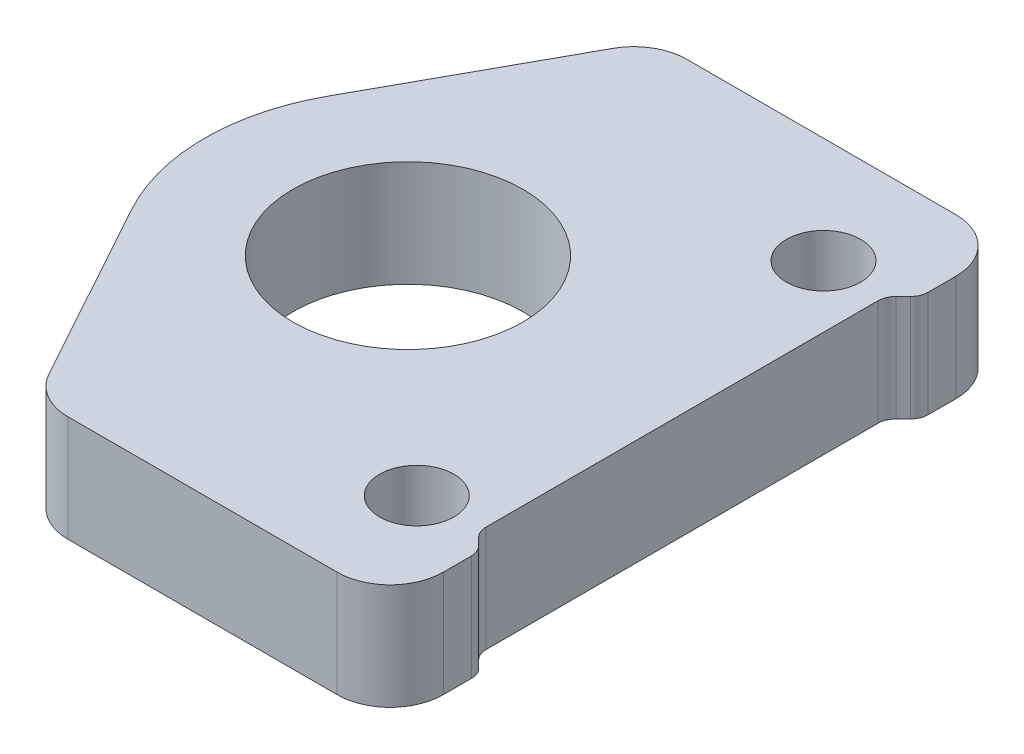
SolidWorks part; units mm, degrees
material "Thornel Mat VMA"
ref_plane "前视基准面" through (0, 0, 0) normal (0, 0, 1) x (1, 0, 0)
ref_plane "上视基准面" through (0, 0, 0) normal (0, 1, 0) x (1, 0, 0)
ref_plane "右视基准面" through (0, 0, 0) normal (1, 0, 0) x (0, 0, -1)
other "Configuration Table"
sketch "草图1" plane through (0, 0, 0) normal (0, 1, 0) x (1, 0, 0)
  line L0 (9.5, -11.5) -> (9.5, 11.5) construction
  line L2 (-14, 17.5) -> (14, 17.5)
  line L3 (-14, 17.5) -> (-14, -17.5)
  line L4 (-14, -17.5) -> (14, -17.5)
  line L5 (14, 17.5) -> (14, -17.5)
  line L6 (-14, 17.5) -> (14, -17.5) construction
  line L7 (-14, -17.5) -> (14, 17.5) construction
  circle A0 centre (9.5, 11.5) radius 2.1
  circle A1 centre (9.5, -11.5) radius 2.1
  circle A2 centre (-2.5, 0) radius 6.505
  point P4 (0, 0)
  dimension "D2" = 4.2
  dimension "D4" = 13.01
  dimension "D1" = 23
  dimension "D3" = 4.5
  dimension "D5" = 12
  dimension "D6" = 28
  dimension "D7" = 35
  dimension "D8" = 11.5
extrude "凸台-拉伸1" add sketch "草图1" along normal blind 6
sketch "草图2" plane through (0, 6, 0) normal (0, 1, 0) x (1, 0, 0)
  line L0 (9.5, 11.5) -> (9.5, -11.5) construction
  line L1 (14, 12.5) -> (13, 11.5)
  line L2 (13, 11.5) -> (18, 11.5) construction
  line L3 (13, 11.5) -> (13, -11.5) construction
  line L4 (13, -11.5) -> (18, -11.5) construction
  line L5 (18, 11.5) -> (18, -11.5) construction
  line L6 (14, -17.5) -> (14, 17.5) construction
  line L7 (13, 11.5) -> (13, -11.5)
  line L8 (13, -11.5) -> (14, -12.5)
  line L9 (14, -12.5) -> (14, 12.5)
  circle A0 centre (9.5, 11.5) radius 3.5 construction
  point P8 (13, 0)
  point P9 (9.5, 0)
  dimension "D2" = 7
  dimension "D1" = 23
  dimension "D3" = 5
  dimension "D4" = 45
  dimension "D5" = 45
extrude "切除-拉伸1" cut sketch "草图2" against normal blind 6
fillet "圆角1" radius 1 4 edges at (14, 3, 12.5) (13, 3, 11.5) (14, 3, -12.5) (13, 3, -11.5)
sketch "草图3" plane through (0, 6, 0) normal (0, 1, 0) x (1, 0, 0)
  line L0 (-14, -17.5) -> (14, -17.5) construction
  line L1 (-6, -17.5) -> (-12.5766, -5.5418)
  line L2 (-6, 17.5) -> (-12.5766, 5.5418)
  line L3 (14, 17.5) -> (-14, 17.5) construction
  line L4 (-14, 17.5) -> (-14, -17.5) construction
  line L5 (-14, -17.5) -> (14, -17.5)
  line L6 (-14, 17.5) -> (-14, -17.5)
  line L7 (14, 17.5) -> (-14, 17.5)
  circle A0 centre (-2.5, 0) radius 11.5
  line M12 (14, 17.5) -> (-14, 17.5)
  line M13 (-14, 17.5) -> (-14, -17.5)
  line M14 (-14, -17.5) -> (14, -17.5)
  dimension "D1" = 23
  dimension "D2" = 8
extrude "切除-拉伸2" cut sketch "草图3" against normal blind 10 contours A0 L6 L1 M14 | A0 L2 M12 M13
fillet "圆角2" radius 3 4 edges at (-6, 3, -17.5) (14, 3, -17.5) (14, 3, 17.5) (-6, 3, 17.5)
